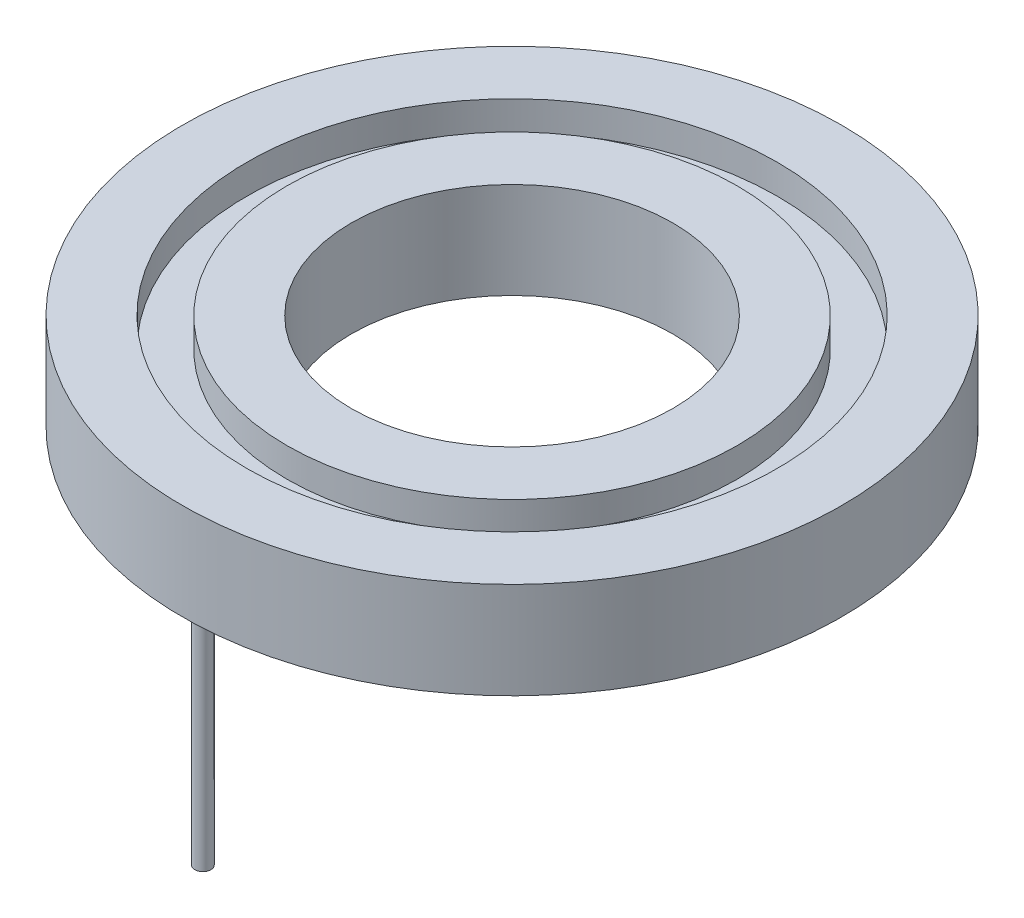
SolidWorks part; units mm, degrees
ref_plane "前视基准面" through (0, 0, 0) normal (0, 0, 1) x (1, 0, 0)
ref_plane "上视基准面" through (0, 0, 0) normal (0, 1, 0) x (1, 0, 0)
ref_plane "右视基准面" through (0, 0, 0) normal (1, 0, 0) x (0, 0, -1)
sketch "草图1" plane through (0, 0, 0) normal (0, 0, 1) x (1, 0, 0)
  line L0 (0, 0) -> (20, 0)
  line L1 (20, 0) -> (28, 0)
  line L2 (28, 0) -> (28, 3.6623)
  line L3 (28, 3.6623) -> (33, 3.6623)
  line L4 (33, 3.6623) -> (33, 0)
  line L5 (33, 0) -> (41, 0)
  line L6 (41, 0) -> (41, 12)
  line L7 (41, 12) -> (33, 12)
  line L8 (33, 12) -> (33, 8.3377)
  line L9 (33, 8.3377) -> (28, 8.3377)
  line L10 (28, 8.3377) -> (28, 11.9615)
  line L11 (28, 11.9615) -> (20, 11.9615)
  line L12 (20, 11.9615) -> (20, 0)
  line L13 (0, 0) -> (0, 17.9596)
  dimension "D1" = 12
  dimension "D2" = 20
  dimension "D3" = 8
  dimension "D4" = 8
  dimension "D5" = 5
  dimension "D6" = 8
  dimension "D7" = 8
revolve "旋转1" add sketch "草图1" angle 360 about L13
sketch "草图2" plane through (0, 0, 0) normal (0, -1, 0) x (1, 0, 0)
  circle A0 centre (0.9966, 39.4582) radius 1
extrude "凸台-拉伸1" add sketch "草图2" along normal blind 27
